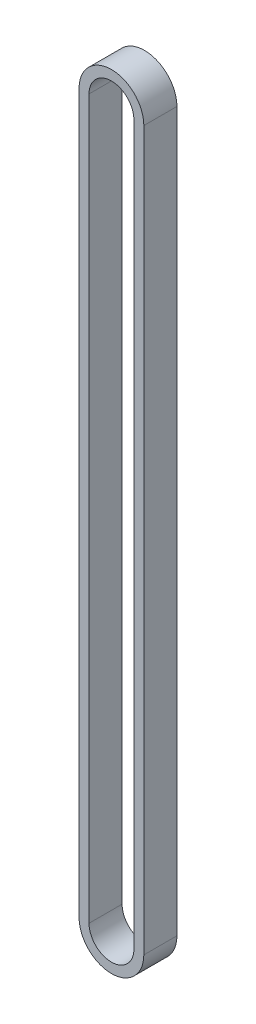
SolidWorks part; units mm, degrees
material "天然橡胶"
ref_plane "前视基准面" through (0, 0, 0) normal (0, 0, 1) x (1, 0, 0)
ref_plane "上视基准面" through (0, 0, 0) normal (0, 1, 0) x (1, 0, 0)
ref_plane "右视基准面" through (0, 0, 0) normal (1, 0, 0) x (0, 0, -1)
other "Configuration Table"
sketch "草图1" plane through (0, 0, 0) normal (0, 0, 1) x (1, 0, 0)
  line L0 (0, -108.5) -> (0, 108.5) construction
  line L1 (-6.78, -108.5) -> (-6.78, 108.5)
  line L2 (6.78, -108.5) -> (6.78, 108.5)
  line L3 (-9.78, -108.5) -> (-9.78, 108.5)
  line L4 (9.78, -108.5) -> (9.78, 108.5)
  arc A0 (-6.78, -108.5) -> (6.78, -108.5) centre (0, -108.5) ccw
  arc A1 (6.78, 108.5) -> (-6.78, 108.5) centre (0, 108.5) ccw
  arc A2 (9.78, 108.5) -> (-9.78, 108.5) centre (0, 108.5) ccw
  arc A3 (-9.78, -108.5) -> (9.78, -108.5) centre (0, -108.5) ccw
  point P2 (0, 0)
  dimension "D2" = 6.78
  dimension "D1" = 217
  dimension "D3" = 3
extrude "凸台-拉伸1" add sketch "草图1" along normal blind 10
